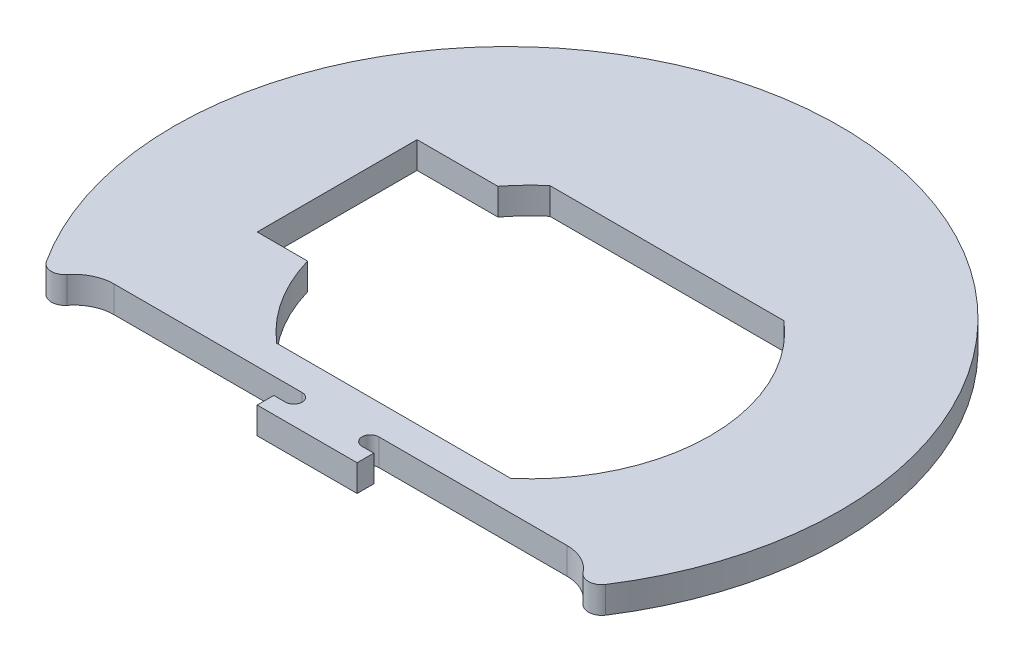
SolidWorks part; units mm, degrees
ref_plane "Front Plane" through (0, 0, 0) normal (0, 0, 1) x (1, 0, 0)
ref_plane "Top Plane" through (0, 0, 0) normal (0, 1, 0) x (1, 0, 0)
ref_plane "Right Plane" through (0, 0, 0) normal (1, 0, 0) x (0, 0, -1)
sketch "Sketch1" plane through (0, 0, 0) normal (0, 1, 0) x (1, 0, 0)
  line L0 (0, 0) -> (0, -74.7107) construction
  line L1 (7.5, -30) -> (-7.5, -30)
  line L2 (-7.5, -30) -> (-7.5, -27.5)
  line L3 (7.5, -30) -> (7.5, -27.5)
  line L4 (-7.5, -27.5) -> (-5.75, -27.5)
  line L5 (7.5, -27.5) -> (5.75, -27.5)
  line L6 (-5.75, -25) -> (-34, -25)
  line L7 (5.75, -25) -> (34, -25)
  line L8 (21.0713, 20.5) -> (-14.0713, 20.5)
  line L9 (21.0713, -20.5) -> (-14.0713, -20.5)
  line L10 (-17.8717, 16.5) -> (-30, 16.5)
  line L11 (-30, 16.5) -> (-30, -7.5)
  line L12 (-30, -7.5) -> (-22.4374, -7.5)
  line L13 (3.5, 0) -> (0, 0) construction
  arc A0 (41.9812, -27.1584) -> (-41.9812, -27.1584) centre (0, 0) ccw
  arc A1 (-5.75, -27.5) -> (-5.75, -25) centre (-5.75, -26.25) ccw
  arc A2 (5.75, -27.5) -> (5.75, -25) centre (5.75, -26.25) cw
  arc A3 (-34, -25) -> (-38.7265, -27.304) centre (-34, -31) ccw
  arc A4 (34, -25) -> (38.7265, -27.304) centre (34, -31) cw
  arc A5 (-38.7265, -27.304) -> (-41.9812, -27.1584) centre (-40.302, -26.072) cw
  arc A6 (38.7265, -27.304) -> (41.9812, -27.1584) centre (40.302, -26.072) ccw
  arc A7 (21.0713, -20.5) -> (21.0713, 20.5) centre (3.5, 0) ccw
  arc A8 (-14.0713, 20.5) -> (-17.8717, 16.5) centre (3.5, 0) ccw
  arc A9 (-22.4374, -7.5) -> (-14.0713, -20.5) centre (3.5, 0) ccw
  point P7 (0, -30)
  dimension "D1" = 50
  dimension "D2" = 9
  dimension "D6" = 6
  dimension "D7" = 2
  dimension "D9" = 27
  dimension "D3" = 15
  dimension "D4" = 68
  dimension "D5" = 2.5
  dimension "D8" = 25
  dimension "D10" = 24
  dimension "D11" = 4
  dimension "D12" = 41
  dimension "D13" = 3.5
  dimension "D14" = 30
  dimension "D15" = 5
extrude "Boss-Extrude1" add sketch "Sketch1" along normal mid plane 4
